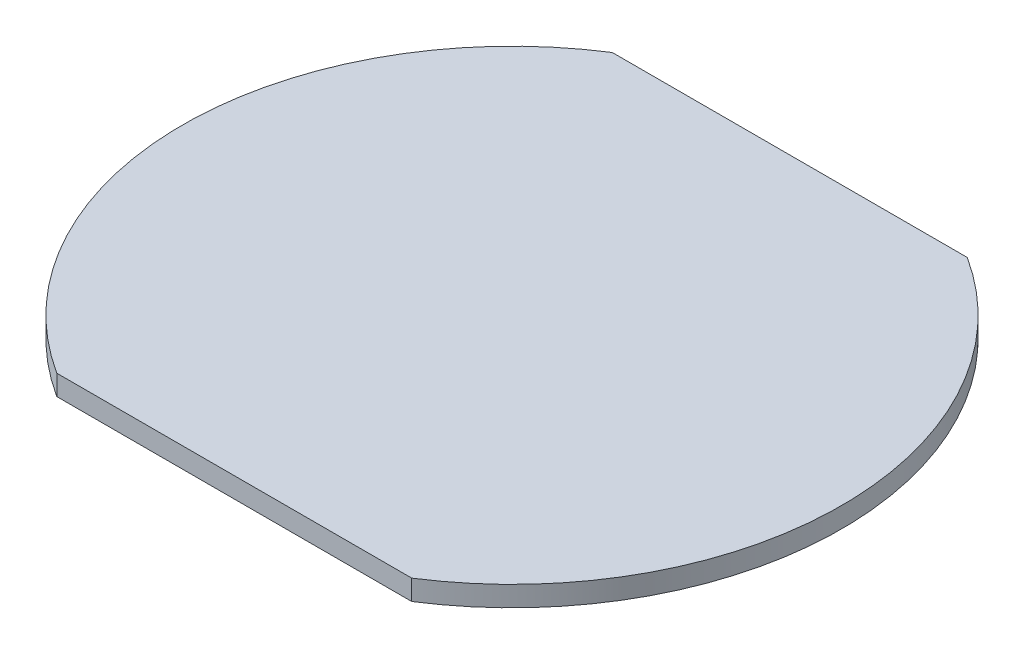
SolidWorks part; units mm, degrees
ref_plane "Front Plane" through (0, 0, 0) normal (0, 0, 1) x (1, 0, 0)
ref_plane "Top Plane" through (0, 0, 0) normal (0, 1, 0) x (1, 0, 0)
ref_plane "Right Plane" through (0, 0, 0) normal (1, 0, 0) x (0, 0, -1)
sketch "Sketch1" plane through (0, 0, 0) normal (0, 1, 0) x (1, 0, 0)
  circle A0 centre (0, 0) radius 32.5
  dimension "D1" = 65
extrude "Boss-Extrude1" add sketch "Sketch1" along normal blind 2
sketch "Sketch2" plane through (0, 2, 0) normal (0, 1, 0) x (1, 0, 0)
  line L0 (17.5, 27.3861) -> (-17.5, 27.3861)
  line L1 (0, 0) -> (-19.5086, 0) construction
  line L2 (17.5, -27.3861) -> (-17.5, -27.3861)
  arc A0 (17.5, 27.3861) -> (-17.5, 27.3861) centre (0, 0) ccw
  circle A1 centre (0, 0) radius 32.5 construction
  arc A2 (17.5, -27.3861) -> (-17.5, -27.3861) centre (0, 0) cw
  point P6 (0, 32.5)
  dimension "D1" = 35
extrude "Cut-Extrude1" cut sketch "Sketch2" against normal up to surface (2 mm away) up to face at (0, 0, 32.5)
